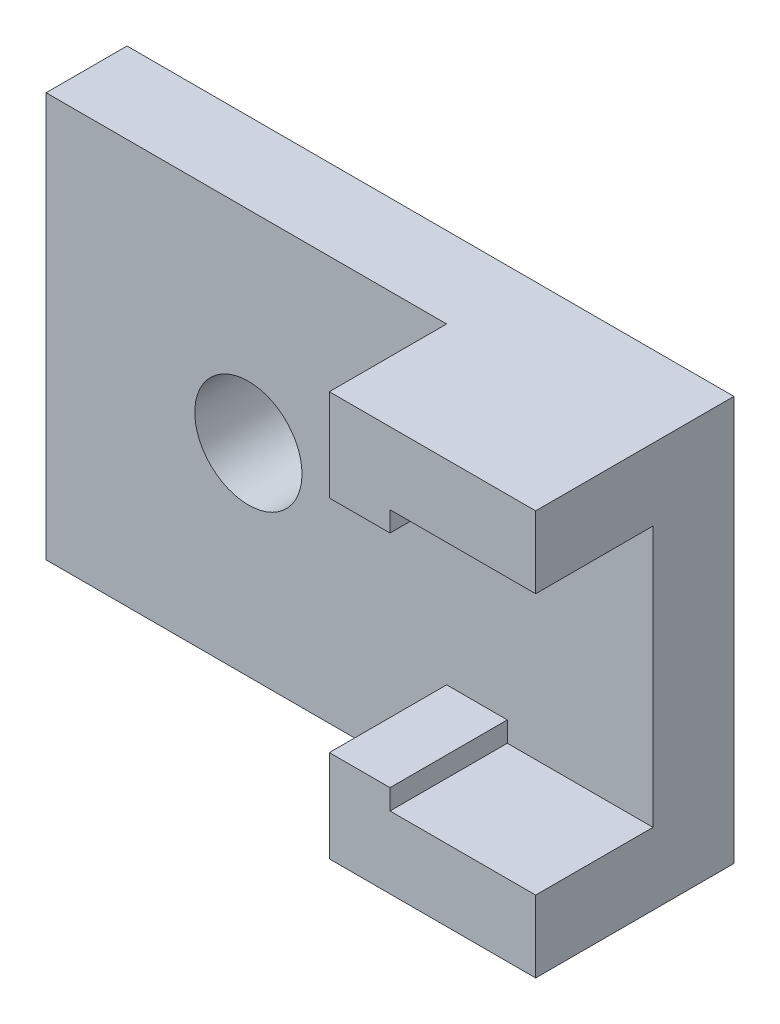
SolidWorks part; units mm, degrees
ref_plane "Front Plane" through (0, 0, 0) normal (0, 0, 1) x (1, 0, 0)
ref_plane "Top Plane" through (0, 0, 0) normal (0, 1, 0) x (1, 0, 0)
ref_plane "Right Plane" through (0, 0, 0) normal (1, 0, 0) x (0, 0, -1)
sketch "Sketch1" plane through (0, 0, 0) normal (0, 0, 1) x (1, 0, 0)
  line L1 (0, 0) -> (30, 0)
  line L2 (0, 0) -> (0, -20)
  line L3 (0, -20) -> (30, -20)
  line L4 (30, 0) -> (30, -20)
  dimension "D1" = 20
  dimension "D2" = 30
extrude "Boss-Extrude1" add sketch "Sketch1" along normal blind 4
sketch "Sketch2" plane through (0, 0, 4) normal (0, 0, 1) x (1, 0, 0)
  line L0 (0, 0) -> (0, -20) construction
  circle A0 centre (10, -10) radius 2.65
  dimension "D1" = 5.3
  dimension "D2" = 10
extrude "Cut-Extrude1" cut sketch "Sketch2" against normal through all
sketch "Sketch3" plane through (0, 0, 4) normal (0, 0, 1) x (1, 0, 0)
  line L1 (22.8, -3.55) -> (29, -3.55)
  line L2 (22.8, -3.55) -> (22.8, -16.45)
  line L3 (22.8, -16.45) -> (29, -16.45)
  line L4 (29, -3.55) -> (29, -16.45)
  line L5 (30, -20) -> (30, 0) construction
  line L7 (22.8, -16.45) -> (30, -16.45)
  line L8 (22.8, -16.45) -> (22.8, -20)
  line L9 (22.8, -20) -> (30, -20)
  line L10 (30, -16.45) -> (30, -20)
  line L11 (22.8, -3.55) -> (30, -3.55)
  line L12 (22.8, -3.55) -> (22.8, 0)
  line L13 (22.8, 0) -> (30, 0)
  line L14 (30, -3.55) -> (30, 0)
  line L15 (22.8, 0) -> (19.8, 0)
  line L16 (22.8, 0) -> (22.8, -4.55)
  line L17 (22.8, -4.55) -> (19.8, -4.55)
  line L18 (19.8, 0) -> (19.8, -4.55)
  line L19 (22.8, -20) -> (19.8, -20)
  line L20 (22.8, -20) -> (22.8, -15.45)
  line L21 (22.8, -15.45) -> (19.8, -15.45)
  line L22 (19.8, -20) -> (19.8, -15.45)
  point P4 (29, -10)
  point P7 (30, -10)
  line M7 (0, -20) -> (30, -20)
  line M8 (30, -20) -> (30, 0)
  line M9 (30, 0) -> (0, 0)
  dimension "D1" = 12.9
  dimension "D2" = 6.2
  dimension "D3" = 0
  dimension "D4" = 1
  dimension "D5" = 3
  dimension "D6" = 3
  dimension "D7" = 1
  dimension "D8" = 1
extrude "Boss-Extrude2" add sketch "Sketch3" along normal blind 5.8 contours L18 L17 L2 L12 M9 | L12 L1 L11 M8 M9 | L22 L8 L2 L21 M7 | L3 L8 L7 M7 M8
equation "\"滑动-垂直孔\" = 0.6"
equation "\"滑动-水平孔\" = 0.3"
equation "\"松动-垂直孔\" = 0.3"
equation "\"松动-水平孔\" = 0.1"
equation "\"正常-垂直孔\" = 0.15"
equation "\"正常-水平孔\" = 0"
equation "\"紧缩-垂直孔\" = 0"
equation "\"紧缩-水平孔\" = -0.1"
equation "\"D1@Sketch2\"=\"松动-垂直孔\"+5"
